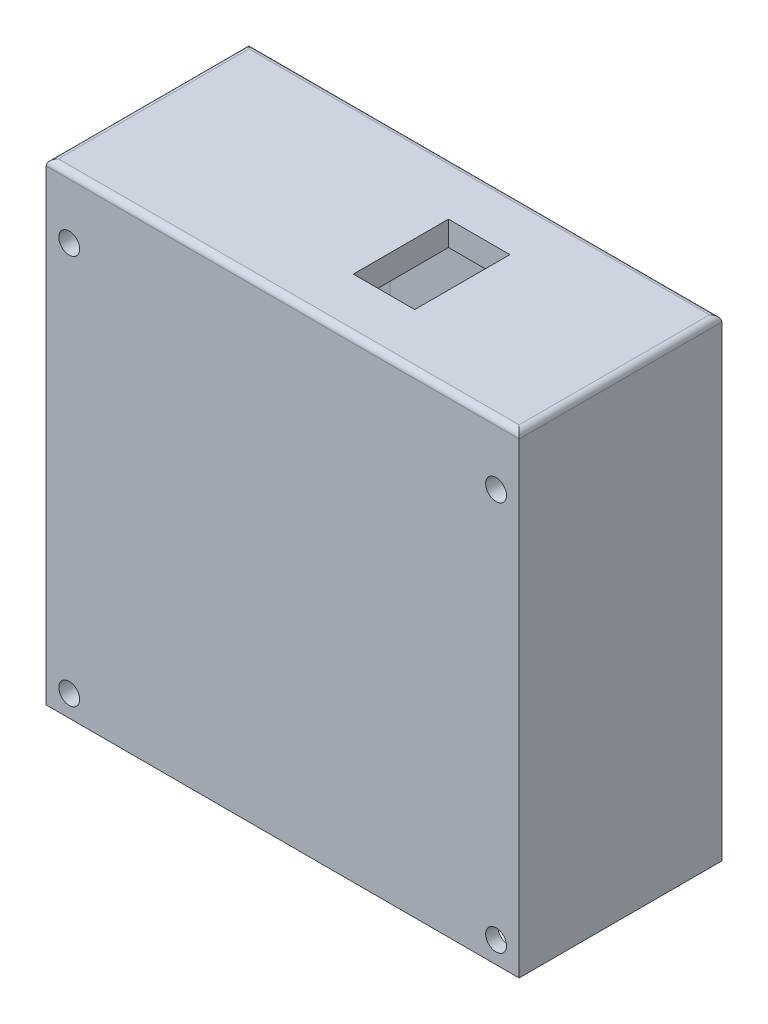
SolidWorks part; units mm, degrees
material "ABS"
ref_plane "Front" through (0, 0, 0) normal (0, 0, 1) x (1, 0, 0)
ref_plane "Top" through (0, 0, 0) normal (0, 1, 0) x (1, 0, 0)
ref_plane "Right" through (0, 0, 0) normal (1, 0, 0) x (0, 0, -1)
sketch "ｽｹｯﾁ1" plane through (0, 0, 0) normal (0, 1, 0) x (1, 0, 0)
  line L1 (38.5, 16.5) -> (-38.5, 16.5)
  line L2 (38.5, 16.5) -> (38.5, -16.5)
  line L3 (38.5, -16.5) -> (-38.5, -16.5)
  line L4 (-38.5, 16.5) -> (-38.5, -16.5)
  line L5 (38.5, 16.5) -> (-38.5, -16.5) construction
  line L6 (38.5, -16.5) -> (-38.5, 16.5) construction
  point P0 (0, 0)
  dimension "D1" = 33
  dimension "D2" = 77
extrude "ﾎﾞｽ - 押し出し1" add sketch "ｽｹｯﾁ1" along normal blind 77
sketch "ｽｹｯﾁ2" plane through (0, 0, 0) normal (0, -1, 0) x (1, 0, 0)
  line L1 (12.75, 13.75) -> (-12.75, 13.75)
  line L2 (18.75, 7.75) -> (18.75, -7.75)
  line L3 (12.75, -13.75) -> (-12.75, -13.75)
  line L4 (-18.75, 7.75) -> (-18.75, -7.75)
  line L5 (18.75, 13.75) -> (-18.75, -13.75) construction
  line L6 (18.75, -13.75) -> (-18.75, 13.75) construction
  arc A0 (12.75, 13.75) -> (18.75, 7.75) centre (12.75, 7.75) cw
  arc A1 (18.75, -7.75) -> (12.75, -13.75) centre (12.75, -7.75) cw
  arc A2 (-12.75, -13.75) -> (-18.75, -7.75) centre (-12.75, -7.75) cw
  arc A3 (-18.75, 7.75) -> (-12.75, 13.75) centre (-12.75, 7.75) cw
  point P0 (0, 0)
  dimension "D3" = 6
  dimension "D1" = 37.5
  dimension "D2" = 27.5
extrude "ｶｯﾄ - 押し出し1" cut sketch "ｽｹｯﾁ2" against normal blind 73
sketch "ｽｹｯﾁ3" plane through (0, 0, 16.5) normal (0, 0, 1) x (1, 0, 0)
  line L0 (-38.5, 0) -> (38.5, 0) construction
  line L1 (-38.5, 77) -> (-38.5, 0) construction
  line L2 (-38.5, 77) -> (38.5, 77) construction
  line L3 (38.5, 77) -> (38.5, 0) construction
  circle A0 centre (34.75, 3.5) radius 1.7
  circle A1 centre (34.75, 67) radius 1.7
  circle A2 centre (-34.75, 67) radius 1.7
  circle A3 centre (-34.75, 3.5) radius 1.7
  dimension "D1" = 3.4
  dimension "D2" = 3.5
  dimension "D3" = 3.75
  dimension "D4" = 10
  dimension "D5" = 3.75
extrude "ｶｯﾄ - 押し出し2" cut sketch "ｽｹｯﾁ3" against normal through all
sketch "ｽｹｯﾁ4" plane through (-38.5, 0, 0) normal (-1, 0, 0) x (0, 0, 1)
  line L0 (-16.5, 0) -> (16.5, 0) construction
  line L1 (6.5, 40) -> (-6.5, 40)
  line L2 (12.5, 34) -> (12.5, 0)
  line L3 (12.5, 0) -> (-12.5, 0)
  line L4 (-12.5, 34) -> (-12.5, 0)
  line L5 (12.5, 40) -> (-12.5, 0) construction
  line L6 (12.5, 0) -> (-12.5, 40) construction
  arc A0 (6.5, 40) -> (12.5, 34) centre (6.5, 34) cw
  arc A1 (-6.5, 40) -> (-12.5, 34) centre (-6.5, 34) ccw
  point P0 (0, 20)
  dimension "D4" = 6
  dimension "D1" = 25
  dimension "D2" = 40
  dimension "D3" = 0
extrude "ｶｯﾄ - 押し出し3" cut sketch "ｽｹｯﾁ4" against normal up to next
sketch "ｽｹｯﾁ5" plane through (0, 73, 0) normal (0, -1, 0) x (1, 0, 0)
  line L0 (18.75, -7.75) -> (18.75, 7.75) construction
  line L1 (2.75, -7.75) -> (12.75, -7.75)
  line L2 (2.75, -7.75) -> (2.75, 7.75)
  line L3 (2.75, 7.75) -> (12.75, 7.75)
  line L4 (12.75, -7.75) -> (12.75, 7.75)
  line L5 (2.75, -7.75) -> (12.75, 7.75) construction
  line L6 (2.75, 7.75) -> (12.75, -7.75) construction
  line L7 (-12.75, -13.75) -> (12.75, -13.75) construction
  line L8 (12.75, 13.75) -> (-12.75, 13.75) construction
  point P0 (7.75, 0)
  dimension "D1" = 6
  dimension "D2" = 6
  dimension "D3" = 6
  dimension "D4" = 10
extrude "ｶｯﾄ - 押し出し4" cut sketch "ｽｹｯﾁ5" against normal through all
sketch "ｽｹｯﾁ6" plane through (0, 0, 0) normal (0, -1, 0) x (-1, 0, 0)
  line L0 (-38.5, 16.5) -> (38.5, 16.5) construction
  line L1 (-20.75, 13.5) -> (-36.5, 13.5)
  line L2 (-20.75, 13.5) -> (-20.75, -14.5)
  line L3 (-20.75, -14.5) -> (-36.5, -14.5)
  line L4 (-36.5, 13.5) -> (-36.5, -14.5)
  line L5 (-20.75, 13.5) -> (-36.5, -14.5) construction
  line L6 (-20.75, -14.5) -> (-36.5, 13.5) construction
  line L7 (-18.75, 7.75) -> (-18.75, -7.75) construction
  line L8 (-38.5, -16.5) -> (-38.5, 16.5) construction
  line L9 (38.5, -16.5) -> (-38.5, -16.5) construction
  point P0 (-28.625, -0.5)
  dimension "D1" = 3
  dimension "D2" = 2
  dimension "D3" = 2
  dimension "D4" = 2
extrude "ｶｯﾄ - 押し出し5" cut sketch "ｽｹｯﾁ6" against normal offset from surface (59.5 mm away) 17.5 up to face at (7.75, 77, 0)
fillet "ﾌｨﾚｯﾄ1" radius 1 4 edges at (0, 77, 16.5) (-38.5, 77, 0) (0, 77, -16.5) (38.5, 77, 0)
